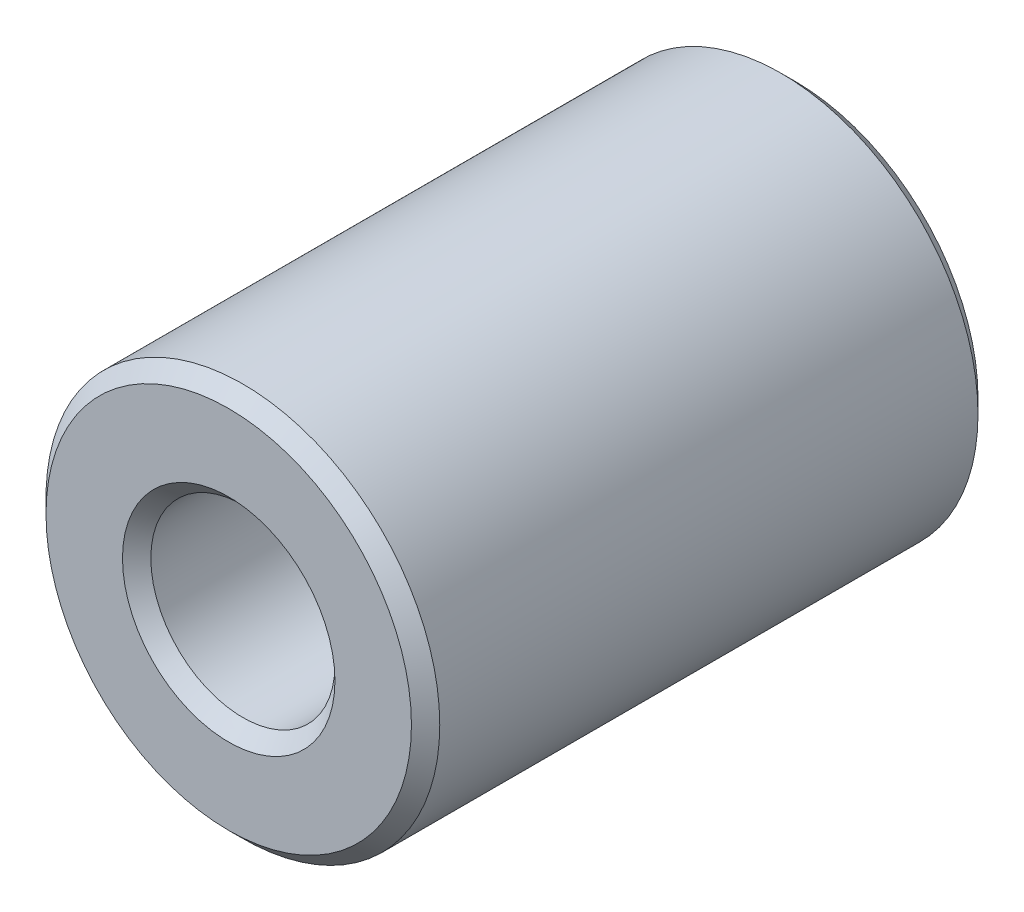
SolidWorks part; units mm, degrees
ref_plane "前视基准面" through (0, 0, 0) normal (0, 0, 1) x (1, 0, 0)
ref_plane "上视基准面" through (0, 0, 0) normal (0, 1, 0) x (1, 0, 0)
ref_plane "右视基准面" through (0, 0, 0) normal (1, 0, 0) x (0, 0, -1)
other "Configuration Table"
sketch "草图1" plane through (0, 0, 0) normal (0, 0, 1) x (1, 0, 0)
  circle A0 centre (0, 0) radius 6.95
  circle A1 centre (0, 0) radius 3.25
  dimension "D1" = 13.9
  dimension "D2" = 6.5
extrude "凸台-拉伸1" add sketch "草图1" along normal blind 20
chamfer "倒角1" distance 0.5 angle 45 4 edges at (3.25, 0, 0) (6.95, 0, 0) (3.25, 0, 20) (6.95, 0, 20)
